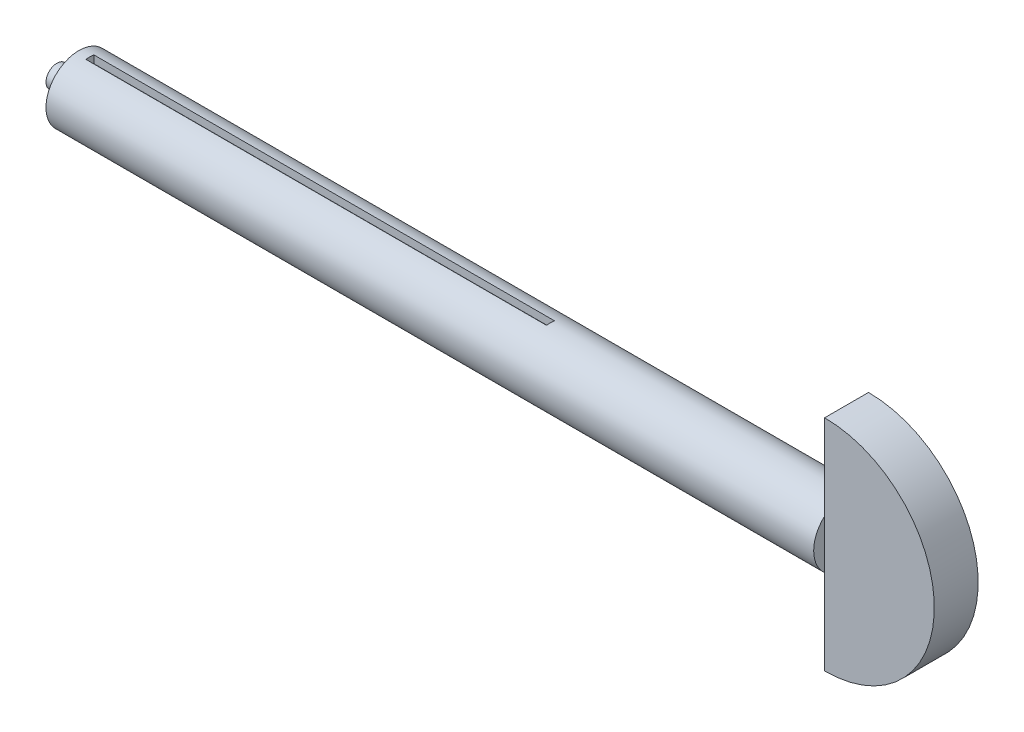
SolidWorks part; units mm, degrees
material "Custom Plastic"
ref_plane "Front Plane" through (0, 0, 0) normal (0, 0, 1) x (1, 0, 0)
ref_plane "Top Plane" through (0, 0, 0) normal (0, 1, 0) x (1, 0, 0)
ref_plane "Right Plane" through (0, 0, 0) normal (1, 0, 0) x (0, 0, -1)
sketch "Sketch1" plane through (0, 0, 0) normal (1, 0, 0) x (0, 0, -1)
  circle A0 centre (0, 0) radius 2.5
  dimension "D1" = 5
extrude "Boss-Extrude1" add sketch "Sketch1" along normal blind 5
sketch "Sketch2" plane through (5, 0, 0) normal (1, 0, 0) x (0, 0, -1)
  circle A0 centre (0, 0) radius 7.5
  dimension "D1" = 15
extrude "Boss-Extrude2" add sketch "Sketch2" along normal blind 175
sketch "Sketch3" plane through (0, 0, 0) normal (0, 0, 1) x (1, 0, 0)
  line L0 (180, -25) -> (180, 25)
  line L2 (180, -7.5) -> (180, 7.5) construction
  arc A0 (180, 25) -> (180, -25) centre (180, 0) cw
  point P2 (180, 0)
  dimension "D1" = 25
  dimension "D2" = 50
extrude "Boss-Extrude3" add sketch "Sketch3" along normal mid plane 10 contours A0 L0
ref_plane "Plane1" through (0, 5.7, 0) normal (0, 1, 0) x (1, 0, 0)
sketch "Sketch4" plane through (0, 5.7, 0) normal (0, 1, 0) x (1, 0, 0)
  line L1 (7.5, 0.9) -> (112.5, 0.9)
  line L2 (7.5, 0.9) -> (7.5, -0.9)
  line L3 (7.5, -0.9) -> (112.5, -0.9)
  line L4 (112.5, 0.9) -> (112.5, -0.9)
  line L6 (5, 7.5) -> (5, -7.5) construction
  point P4 (7.5, 0)
  dimension "D1" = 1.8
  dimension "D2" = 105
  dimension "D3" = 2.5
extrude "Cut-Extrude1" cut sketch "Sketch4" along normal blind 1.8
mirror "Mirror1" about plane through (0, 0, 0) normal (0, 1, 0) of "Cut-Extrude1"
